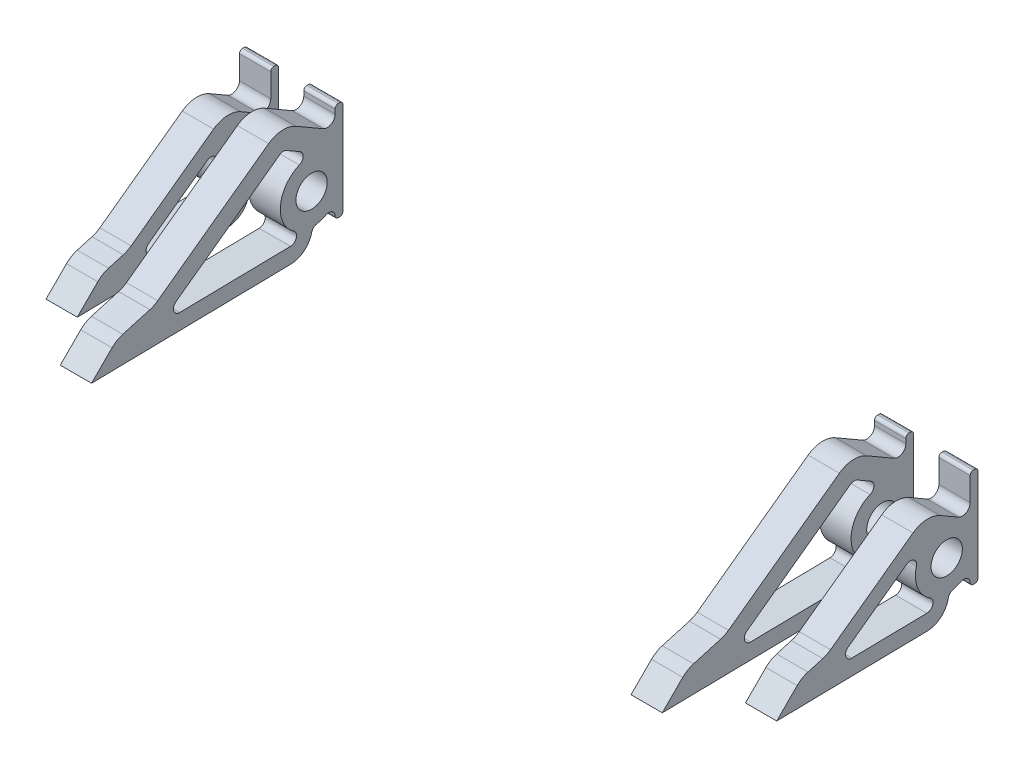
SolidWorks part; units mm, degrees
material "AR500"
ref_plane "Front Plane" through (0, 0, 0) normal (0, 0, 1) x (1, 0, 0)
ref_plane "Top Plane" through (0, 0, 0) normal (0, 1, 0) x (1, 0, 0)
ref_plane "Right Plane" through (0, 0, 0) normal (1, 0, 0) x (0, 0, -1)
ref_plane "Plane1" through (57.8922, 0, 0) normal (1, 0, 0) x (0, 0, -1)
ref_plane "Plane2" through (70.9415, 0, 0) normal (1, 0, 0) x (0, 0, -1)
sketch "Sketch1" plane through (57.8922, 0, 0) normal (1, 0, 0) x (0, 0, -1)
  line L0 (-231.8557, -25.4) -> (-180.8652, -24.51)
  line L1 (-180.8652, -24.51) -> (-180.8652, -6.48)
  line L3 (-219.1557, -18.135) -> (-226.7757, -20.32)
  line L4 (-226.7757, -20.32) -> (-231.8557, -25.4)
  line L5 (0, -25.4) -> (-231.8557, -25.4) construction
  line L7 (-193.2625, 0.6775) -> (-180.8652, -6.48)
  line L8 (-219.1557, -18.135) -> (-193.2625, 0.6775)
  circle A1 centre (-187.2152, -13.97) radius 3.175 construction
  circle A2 centre (-187.2152, -13.97) radius 3.175
  circle A3 centre (-187.2152, -13.97) radius 6.35 construction
  dimension "D3" = 3.175
  dimension "D1" = 1
  dimension "D2" = 45
  dimension "D4" = 15
  dimension "D5" = 5.08
  dimension "D6" = 60
  dimension "D7" = 35
  dimension "D8" = 25.4
  dimension "D9" = 12.7
extrude "Boss-Extrude1" add sketch "Sketch1" along normal mid plane 6.35
sketch "Sketch5" plane through (70.9415, 0, 0) normal (1, 0, 0) x (0, 0, -1)
  line L0 (-221.6957, -25.4) -> (-180.8652, -24.6873)
  line L1 (-180.8652, -24.6873) -> (-180.8652, -10.3038)
  line L2 (-180.8652, -24.51) -> (-180.8652, -6.48) construction
  line L3 (-180.8652, -10.3038) -> (-191.3793, -4.2335)
  line L4 (-191.3793, -4.2335) -> (-211.5024, -18.8538)
  line L5 (-231.8557, -25.4) -> (-180.8652, -24.51) construction
  line L6 (-193.2625, 0.6775) -> (-219.1557, -18.135) construction
  line L7 (-180.8652, -6.48) -> (-193.2625, 0.6775) construction
  line L8 (-211.5024, -18.8538) -> (-216.6157, -20.32)
  line L9 (-216.6157, -20.32) -> (-221.6957, -25.4)
  line L10 (-226.7757, -20.32) -> (-231.8557, -25.4) construction
  line L11 (-219.1557, -18.135) -> (-226.7757, -20.32) construction
  circle A0 centre (-187.2152, -13.97) radius 6.35 construction
  circle A1 centre (-187.2152, -13.97) radius 3.175
  circle A2 centre (-187.2152, -13.97) radius 3.175 construction
  dimension "D2" = 5.08
  dimension "D1" = 10.16
extrude "Boss-Extrude3" add sketch "Sketch5" along normal mid plane 6.35 separate body
fillet "Fillet1" radius 5.08 3 edges at (57.8922, 0.6775, 193.2625) (57.8922, -18.135, 219.1557) (57.8922, -20.32, 226.7757)
fillet "Fillet4" radius 5.08 3 edges at (70.9415, -4.2335, 191.3793) (70.9415, -20.32, 216.6157) (70.9415, -18.8538, 211.5024)
sketch "Sketch3" plane through (61.0672, 0, 0) normal (1, 0, 0) x (0, 0, -1)
  line L0 (-180.8652, -24.51) -> (-180.8652, -6.48) construction
  line L1 (-180.8652, -21.335) -> (-182.4527, -21.335)
  line L2 (-182.4527, -21.335) -> (-182.4527, -20.7425)
  line L14 (-231.8557, -25.4) -> (-180.8652, -24.51) construction
  line L15 (-180.8652, -24.51) -> (-180.8652, -21.335)
  line L17 (-180.8652, -24.51) -> (-191.4528, -24.6948)
  line L20 (-184.6752, -8.6797) -> (-192.3104, -4.2715)
  line L21 (-193.6919, -4.3439) -> (-216.1915, -20.6909)
  line L23 (-217.2167, -21.3339) -> (-184.6752, -20.7659)
  line L24 (-184.6752, -20.7659) -> (-184.6752, -8.6797)
  line L25 (-189.5626, -5.858) -> (-192.3104, -4.2715)
  line L26 (-193.6919, -4.3439) -> (-214.7101, -19.6146)
  line L28 (-213.9415, -21.9118) -> (-191.5082, -21.5202)
  circle A0 centre (-187.2152, -13.97) radius 6.35
  arc A4 (-192.3104, -4.2715) -> (-193.6919, -4.3439) centre (-192.9454, -5.3714) ccw
  arc A5 (-192.3104, -4.2715) -> (-193.6919, -4.3439) centre (-192.9454, -5.3714) ccw
  arc A6 (-217.2167, -21.3339) -> (-216.1915, -20.6909) centre (-221.4169, -13.4987) ccw
  arc A12 (-213.9415, -21.9118) -> (-214.7101, -19.6146) centre (-213.9637, -20.642) cw
  arc A13 (-190.8112, -19.2037) -> (-191.5082, -21.5202) centre (-191.5304, -20.2504) cw
  arc A14 (-189.7005, -8.1266) -> (-189.5626, -5.858) centre (-190.1976, -6.9579) ccw
  arc A19 (-182.4527, -20.7425) -> (-184.3048, -19.6138) centre (-183.7227, -20.7425) ccw
  arc A20 (-191.4528, -24.6948) -> (-187.1902, -21.2101) centre (-191.5304, -20.2504) ccw
  arc A21 (-187.1902, -21.2101) -> (-186.161, -20.2319) centre (-185.9501, -21.4843) cw
  dimension "D1" = 12.7
  dimension "D4" = 1.27
  dimension "D5" = 3.175
  dimension "D6" = 1.5875
  dimension "D3" = 3.175
  dimension "D2" = 3.81
extrude "Cut-Extrude1" cut sketch "Sketch3" against normal up to next (6.35 mm away)
sketch "Sketch6" plane through (74.1165, 0, 0) normal (1, 0, 0) x (0, 0, -1)
  line L2 (-192.182, -8.7412) -> (-208.9115, -20.8959)
  line L3 (-192.182, -8.7412) -> (-210.4705, -22.0286)
  line L4 (-180.8652, -24.6873) -> (-180.8652, -10.3038) construction
  line L5 (-221.7511, -22.2255) -> (-180.9206, -21.5128)
  line L6 (-210.4705, -22.0286) -> (-191.2453, -21.693)
  line L7 (-180.8652, -21.335) -> (-182.4527, -21.335)
  line L8 (-182.4527, -21.335) -> (-182.4527, -20.7425)
  line L9 (-221.6957, -25.4) -> (-180.8652, -24.6873) construction
  line L10 (-180.8652, -21.335) -> (-180.8652, -24.6873)
  line L11 (-180.8652, -24.6873) -> (-191.2453, -24.8685)
  arc A1 (-206.4432, -21.9583) -> (-207.2118, -19.661) centre (-206.4653, -20.6885) cw
  arc A2 (-190.1098, -8.6326) -> (-192.182, -8.7412) centre (-191.0623, -10.2824) ccw
  arc A3 (-190.1098, -8.6326) -> (-192.182, -8.7412) centre (-191.0623, -10.2824) ccw
  circle A4 centre (-187.2152, -13.97) radius 6.35
  circle A5 centre (-187.2152, -13.97) radius 3.175 construction
  arc A6 (-191.2453, -21.693) -> (-190.5921, -19.3477) centre (-191.2675, -20.4232) ccw
  arc A7 (-193.363, -12.3804) -> (-195.3391, -11.035) centre (-194.5926, -12.0624) ccw
  arc A8 (-182.4527, -20.7425) -> (-184.3048, -19.6138) centre (-183.7227, -20.7425) ccw
  arc A9 (-191.2453, -24.8685) -> (-186.8236, -20.3079) centre (-191.2675, -20.4232) ccw
  arc A10 (-186.891, -21.2028) -> (-185.9031, -20.183) centre (-185.6407, -21.4256) cw
  line M10 (-180.8652, -24.6873) -> (-180.8652, -10.3038)
  dimension "D3" = 1.27
  dimension "D4" = 1.5875
  dimension "D1" = 3.175
  dimension "D2" = 3.175
extrude "Cut-Extrude2" cut sketch "Sketch6" against normal blind 6.35 contours A4 A7 L3 A1 L6 A6 | A9 L11 L7 L8 A8 A4 M10
sketch "Sketch4" plane through (61.0672, 0, 0) normal (1, 0, 0) x (0, 0, -1)
  line L0 (-180.8652, -6.48) -> (-180.8652, -1.27)
  line L1 (-180.8652, -1.27) -> (-182.4527, -1.27)
  line L2 (-182.4527, -1.27) -> (-182.4527, -5.5635)
  line L3 (-180.8652, -6.48) -> (-190.4054, -0.972) construction
  line L4 (-182.4527, -5.5635) -> (-180.8652, -6.48)
  circle A0 centre (-187.2152, -13.97) radius 3.175 construction
  circle A1 centre (-187.2152, -13.97) radius 3.175 construction
  dimension "D1" = 12.7
extrude "Boss-Extrude2" add sketch "Sketch4" against normal up to surface (6.35 mm away) up to face at (54.7172, -13.97, 184.0402)
sketch "Sketch7" plane through (74.1165, 0, 0) normal (1, 0, 0) x (0, 0, -1)
  line L0 (-180.8652, -10.3038) -> (-180.8652, -1.27)
  line L1 (-180.8652, -21.335) -> (-180.8652, -1.27) construction
  line L2 (-180.8652, -1.27) -> (-182.4527, -1.27)
  line L3 (-182.4527, -1.27) -> (-182.4527, -5.5635) construction
  line L4 (-182.4527, -1.27) -> (-182.4527, -9.3873)
  line L5 (-180.8652, -10.3038) -> (-188.5223, -5.883) construction
  line L6 (-182.4527, -9.3873) -> (-180.8652, -10.3038)
  point P11 (-180.8652, -3.177)
extrude "Boss-Extrude4" add sketch "Sketch7" against normal up to surface (6.35 mm away) up to face at (67.7665, -18.328, 195.629)
fillet "Fillet2" radius 1.5875 1 edges at (57.8922, -5.5635, 182.4527)
fillet "Fillet3" radius 0.635 4 edges at (57.8922, -21.335, 182.4527) (57.8922, -21.335, 180.8652) (57.8922, -1.27, 180.8652) (57.8922, -1.27, 182.4527)
fillet "Fillet5" radius 1.5875 1 edges at (70.9415, -9.3873, 182.4527)
fillet "Fillet6" radius 0.635 4 edges at (70.9415, -1.27, 180.8652) (70.9415, -1.27, 182.4527) (70.9415, -21.335, 180.8652) (70.9415, -21.335, 182.4527)
mirror "Mirror1" about plane through (0, 0, 0) normal (1, 0, 0) of bodies 103 111 104 107
